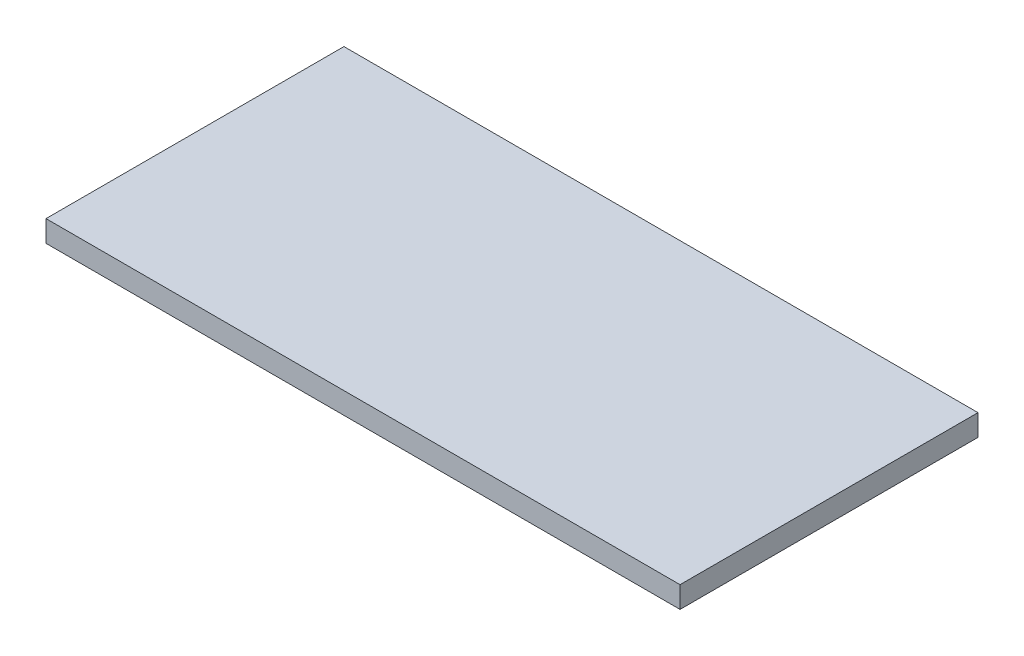
SolidWorks part; units mm, degrees
material "Pine"
ref_plane "Front Plane" through (0, 0, 0) normal (0, 0, 1) x (1, 0, 0)
ref_plane "Top Plane" through (0, 0, 0) normal (0, 1, 0) x (1, 0, 0)
ref_plane "Right Plane" through (0, 0, 0) normal (1, 0, 0) x (0, 0, -1)
sketch "Sketch1" plane through (0, 0, 0) normal (0, 1, 0) x (1, 0, 0)
  line L1 (-266, 125) -> (266, 125)
  line L2 (-266, 125) -> (-266, -125)
  line L3 (-266, -125) -> (266, -125)
  line L4 (266, 125) -> (266, -125)
  line L5 (-266, 125) -> (266, -125) construction
  line L6 (-266, -125) -> (266, 125) construction
  point P0 (0, 0)
  dimension "D1" = 532
  dimension "D2" = 250
extrude "Boss-Extrude1" add sketch "Sketch1" along normal blind 18
